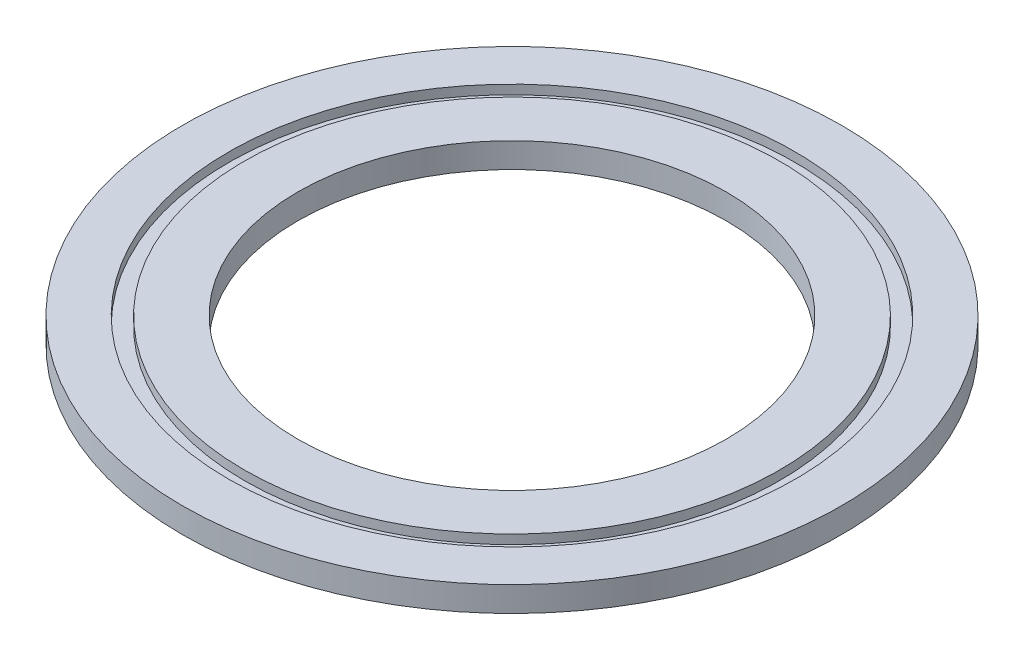
SolidWorks part; units mm, degrees
material "Pine"
ref_plane "Front Plane" through (0, 0, 0) normal (0, 0, 1) x (1, 0, 0)
ref_plane "Top Plane" through (0, 0, 0) normal (0, 1, 0) x (1, 0, 0)
ref_plane "Right Plane" through (0, 0, 0) normal (1, 0, 0) x (0, 0, -1)
sketch "Sketch1" plane through (0, 0, 0) normal (0, 1, 0) x (1, 0, 0)
  circle A0 centre (0, 0) radius 250
  circle A1 centre (0, 0) radius 162.5
  dimension "D1" = 500
  dimension "D2" = 325
extrude "Boss-Extrude1" add sketch "Sketch1" along normal blind 19
sketch "Sketch2" plane through (0, 19, 0) normal (0, 1, 0) x (1, 0, 0)
  circle A0 centre (0, 0) radius 215
  circle A1 centre (0, 0) radius 203
  dimension "D1" = 430
  dimension "D2" = 406
extrude "Cut-Extrude1" cut sketch "Sketch2" against normal blind 7
